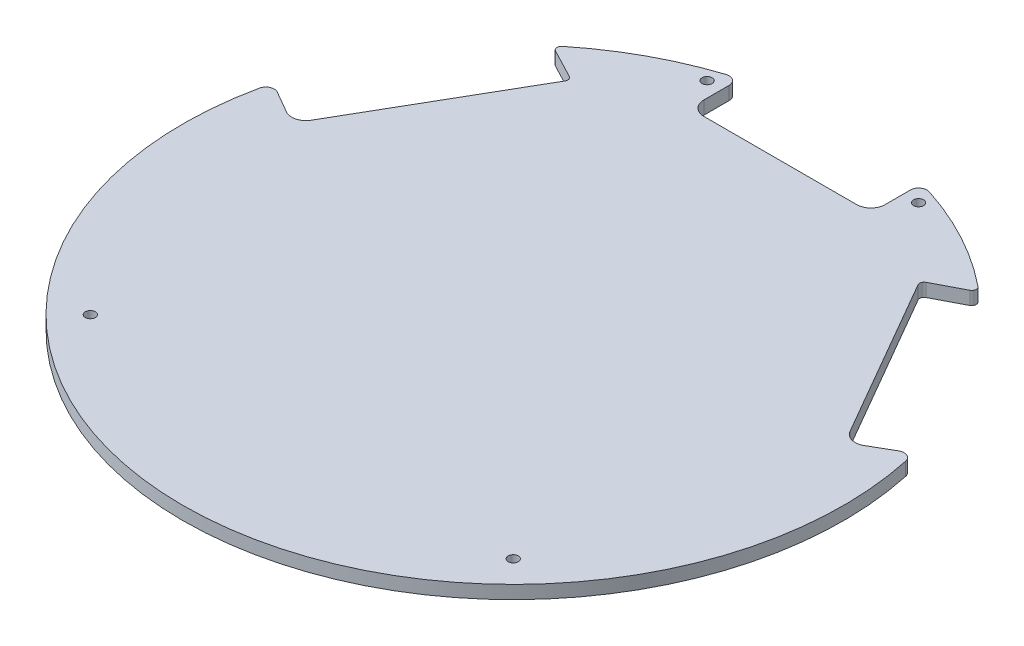
SolidWorks part; units mm, degrees
ref_plane "Front Plane" through (0, 0, 0) normal (0, 0, 1) x (1, 0, 0)
ref_plane "Top Plane" through (0, 0, 0) normal (0, 1, 0) x (1, 0, 0)
ref_plane "Right Plane" through (0, 0, 0) normal (1, 0, 0) x (0, 0, -1)
sketch "Sketch1" plane through (0, 0, 0) normal (0, 1, 0) x (1, 0, 0)
  line L0 (0, 80.1116) -> (0, -80.7693) construction
  line L1 (-87.7547, 0) -> (95.347, 0) construction
  line L2 (-17.353, 60.6071) -> (17.353, 60.6071) construction
  line L3 (-17.353, 60.6071) -> (17.353, 60.6071)
  line L5 (-20.5723, 63.8263) -> (-20.5723, 69.573)
  line L7 (17.353, 60.6071) -> (-17.353, 60.6071)
  line L8 (20.5723, 63.8263) -> (20.5723, 69.573)
  line L9 (65.5614, 14.097) -> (70.5382, 16.9704)
  line L10 (61.1638, 15.2754) -> (40.0698, 51.8111)
  line L11 (-40.4729, 53.1975) -> (-47.032, 56.6229)
  line L12 (40.4729, 53.1975) -> (47.032, 56.6229)
  line L20 (-61.1638, 15.2754) -> (-40.0698, 51.8111)
  line L22 (-65.5614, 14.097) -> (-70.5382, 16.9704)
  line L24 (-43.8107, -45.3317) -> (-63.8107, -10.6907) [skipped]
  line L25 (-44.9891, -49.7293) -> (-49.9659, -52.6026) [skipped]
  line L27 (17.0511, -60.6071) -> (-1.3228, -60.6071) [skipped]
  line L28 (20.5723, -63.8263) -> (20.5723, -69.573) [skipped]
  line L30 (61.1638, -15.2754) -> (41.1638, -49.9164) [skipped]
  line L31 (65.5614, -14.097) -> (70.5382, -16.9704) [skipped]
  line L33 (43.8107, 45.3317) -> (63.8107, 10.6907) [skipped]
  line L34 (44.9891, 49.7293) -> (49.9659, 52.6026) [skipped]
  arc A0 (-23.0437, 71.3722) -> (-27.5772, 69.746) centre (0, 0) ccw
  arc A2 (-74.1904, 10.9905) -> (74.1904, 10.9905) centre (0, 0) ccw
  arc A4 (-20.5723, 63.8263) -> (-17.353, 60.6071) centre (-17.353, 63.8263) ccw
  arc A6 (-20.5723, 69.573) -> (-23.0437, 71.3722) centre (-22.4629, 69.573) ccw
  arc A10 (22.9895, 71.3896) -> (27.5772, 69.746) centre (0, 0) cw
  arc A11 (20.5723, 63.8263) -> (17.353, 60.6071) centre (17.353, 63.8263) cw
  arc A12 (20.5723, 69.573) -> (23.0437, 71.3722) centre (22.4629, 69.573) cw
  arc A13 (27.5772, 69.746) -> (22.9895, 71.3896) centre (0, 0) ccw
  circle A14 centre (-24, 68) radius 1.15
  arc A18 (-74.1904, -10.9905) -> (-73.332, 15.7296) centre (0, 0) cw
  arc A19 (70.5382, 16.9704) -> (73.332, 15.7296) centre (71.4835, 15.3331) cw
  arc A20 (65.5614, 14.097) -> (61.1638, 15.2754) centre (63.9517, 16.885) cw
  arc A21 (73.32, 15.7853) -> (74.1904, 10.9905) centre (0, 0) cw
  arc A22 (-40.4729, 53.1975) -> (-40.0698, 51.8111) centre (-40.9358, 52.3111) cw
  arc A23 (40.4729, 53.1975) -> (40.0698, 51.8111) centre (40.9358, 52.3111) ccw
  circle A24 centre (24, 68) radius 1.15
  arc A25 (47.1984, 58.2864) -> (46.6132, 58.7555) centre (0, 0) ccw
  arc A26 (-47.032, 56.6229) -> (-47.1984, 58.2864) centre (-46.5691, 57.5093) cw
  arc A27 (-48.3673, 57.3202) -> (-23.0437, 71.3722) centre (0, 0) cw
  arc A28 (73.32, 15.7853) -> (74.1904, -10.9905) centre (0, 0) cw
  arc A29 (50.3305, -55.6043) -> (46.6132, -58.7555) centre (0, 0) cw
  arc A30 (47.032, 56.6229) -> (47.1984, 58.2864) centre (46.5691, 57.5093) ccw
  arc A31 (22.9895, 71.3896) -> (47.1984, 58.2864) centre (0, 0) cw
  circle A32 centre (-48, -48) radius 1.15
  arc A33 (73.332, -15.7296) -> (74.1904, -10.9905) centre (0, 0) ccw
  circle A34 centre (48, -48) radius 1.15
  arc A37 (-22.9895, -71.3896) -> (-27.5772, -69.746) centre (0, 0) cw
  arc A41 (23.0437, -71.3722) -> (27.5772, -69.746) centre (0, 0) ccw
  arc A45 (-73.32, -15.7853) -> (-74.1904, -10.9905) centre (0, 0) cw
  arc A49 (-50.2882, -55.6425) -> (-46.6132, -58.7555) centre (0, 0) ccw
  arc A53 (-47.1984, 58.2864) -> (-46.6132, 58.7555) centre (0, 0) cw
  arc A55 (-65.5614, 14.097) -> (-61.1638, 15.2754) centre (-63.9517, 16.885) ccw
  arc A56 (-70.5382, 16.9704) -> (-73.332, 15.7296) centre (-71.4835, 15.3331) ccw
  arc A57 (-73.332, 15.7296) -> (-74.1904, 10.9905) centre (0, 0) ccw
  arc A62 (-44.9891, -49.7293) -> (-43.8107, -45.3317) centre (-46.5987, -46.9413) ccw [skipped]
  arc A63 (-49.9659, -52.6026) -> (-50.2882, -55.6425) centre (-49.0206, -54.2399) ccw [skipped]
  arc A68 (20.5723, -63.8263) -> (17.353, -60.6071) centre (17.353, -63.8263) ccw [skipped]
  arc A69 (20.5723, -69.573) -> (23.0437, -71.3722) centre (22.4629, -69.573) ccw [skipped]
  arc A74 (65.5614, -14.097) -> (61.1638, -15.2754) centre (63.9517, -16.885) ccw [skipped]
  arc A75 (70.5382, -16.9704) -> (73.332, -15.7296) centre (71.4835, -15.3331) ccw [skipped]
  arc A80 (44.9891, 49.7293) -> (43.8107, 45.3317) centre (46.5987, 46.9413) ccw [skipped]
  arc A81 (49.9659, 52.6026) -> (50.2882, 55.6425) centre (49.0206, 54.2399) ccw [skipped]
  point P136 (0, 0)
  dimension "D1" = 150
  dimension "D4" = 41.1446
  dimension "D2" = 2.3
  dimension "D3" = 1
  dimension "D5" = 1
  dimension "D6" = 2.3
  dimension "D7" = 24
  dimension "D8" = 68
  dimension "D9" = 48
  dimension "D10" = 6
  dimension "D11" = 48
extrude "Boss-Extrude2" add sketch "Sketch1" along normal blind 3
